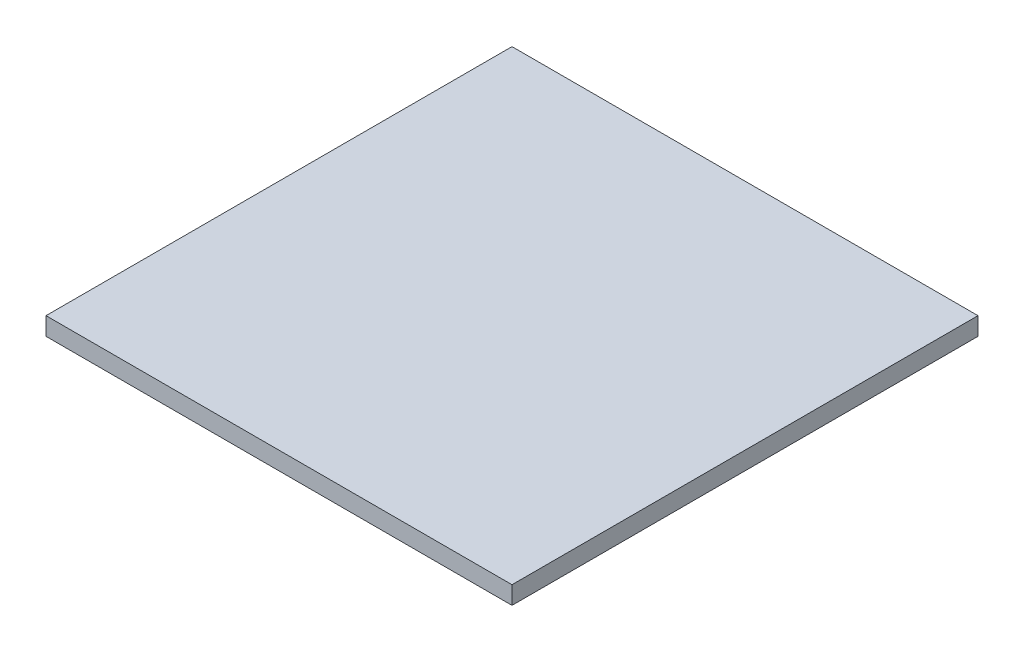
SolidWorks part; units mm, degrees
ref_plane "Front Plane" through (0, 0, 0) normal (0, 0, 1) x (1, 0, 0)
ref_plane "Top Plane" through (0, 0, 0) normal (0, 1, 0) x (1, 0, 0)
ref_plane "Right Plane" through (0, 0, 0) normal (1, 0, 0) x (0, 0, -1)
sketch "Sketch1" plane through (0, 0, 0) normal (0, 1, 0) x (1, 0, 0)
  line L1 (4160, -4160) -> (-4160, -4160)
  line L2 (4160, -4160) -> (4160, 4160)
  line L3 (4160, 4160) -> (-4160, 4160)
  line L4 (-4160, -4160) -> (-4160, 4160)
  line L5 (4160, -4160) -> (-4160, 4160) construction
  line L6 (4160, 4160) -> (-4160, -4160) construction
  point P0 (0, 0)
  dimension "D1" = 8320
  dimension "D2" = 8320
extrude "Boss-Extrude1" add sketch "Sketch1" along normal blind 320
sketch "Sketch2" plane through (0, 320, 0) normal (0, 1, 0) x (1, 0, 0)
  line L0 (-2927.0597, 4120) -> (-2927.0597, -4120)
  line L1 (4160, 4160) -> (-4160, 4160) construction
  line L2 (-4160, -4160) -> (4160, -4160) construction
  dimension "D1" = 40
  dimension "D2" = 40
